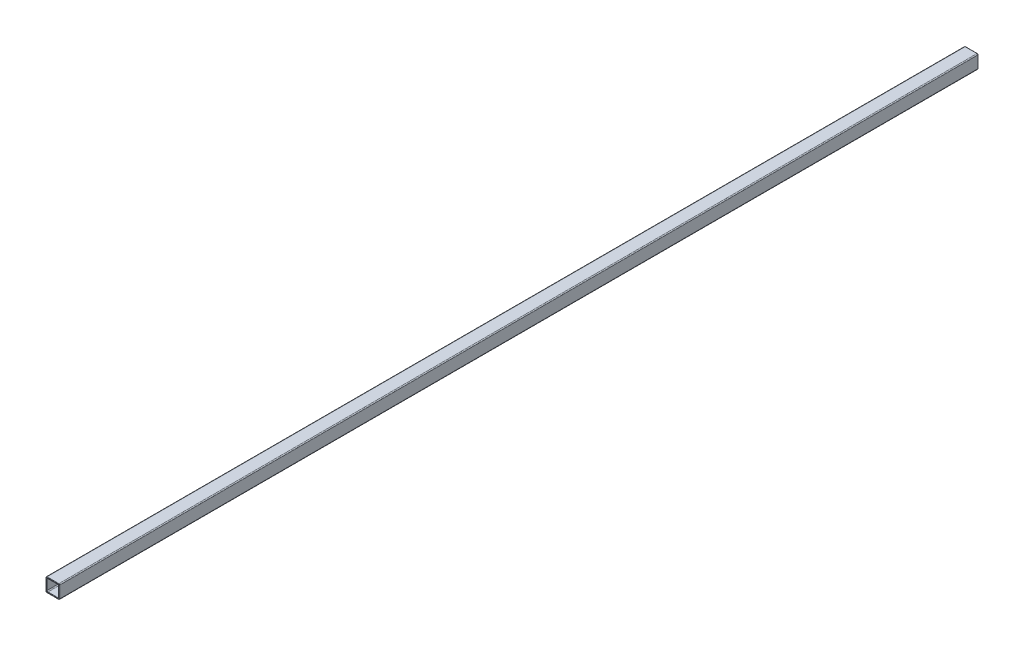
SolidWorks part; units mm, degrees
material "ASTM A500 Grade B Steel"
ref_plane "Front Plane" through (0, 0, 0) normal (0, 0, 1) x (1, 0, 0)
ref_plane "Top Plane" through (0, 0, 0) normal (0, 1, 0) x (1, 0, 0)
ref_plane "Right Plane" through (0, 0, 0) normal (1, 0, 0) x (0, 0, -1)
sketch "Sketch1" plane through (0, 0, 0) normal (0, 0, 1) x (1, 0, 0)
  line L0 (5.3086, -2.7686) -> (32.7914, -2.7686)
  line L1 (2.54, 0) -> (35.56, 0)
  line L2 (0, -2.54) -> (0, -35.56)
  line L3 (2.54, -38.1) -> (35.56, -38.1)
  line L4 (38.1, -2.54) -> (38.1, -35.56)
  line L5 (35.3314, -5.3086) -> (35.3314, -32.7914)
  line L6 (5.3086, -35.3314) -> (32.7914, -35.3314)
  line L7 (2.7686, -5.3086) -> (2.7686, -32.7914)
  line L8 (0, 0) -> (0, -38.1) construction
  line L9 (0, -38.1) -> (38.1, -38.1) construction
  line L10 (38.1, 0) -> (38.1, -38.1) construction
  line L11 (2.7686, -2.7686) -> (2.7686, -35.3314) construction
  line L12 (2.7686, -35.3314) -> (35.3314, -35.3314) construction
  line L13 (35.3314, -2.7686) -> (35.3314, -35.3314) construction
  line L14 (2.7686, -2.7686) -> (35.3314, -2.7686) construction
  line L15 (0, 0) -> (38.1, 0) construction
  arc A0 (0, -35.56) -> (2.54, -38.1) centre (2.54, -35.56) ccw
  arc A1 (38.1, -35.56) -> (35.56, -38.1) centre (35.56, -35.56) cw
  arc A2 (2.7686, -32.7914) -> (5.3086, -35.3314) centre (5.3086, -32.7914) ccw
  arc A3 (32.7914, -35.3314) -> (35.3314, -32.7914) centre (32.7914, -32.7914) ccw
  arc A4 (35.3314, -5.3086) -> (32.7914, -2.7686) centre (32.7914, -5.3086) ccw
  arc A5 (38.1, -2.54) -> (35.56, 0) centre (35.56, -2.54) ccw
  arc A6 (0, -2.54) -> (2.54, 0) centre (2.54, -2.54) cw
  arc A7 (5.3086, -2.7686) -> (2.7686, -5.3086) centre (5.3086, -5.3086) ccw
  point P12 (0, -38.1)
  dimension "D4" = 2.54
  dimension "D3" = 2.7686
extrude "Boss-Extrude1" add sketch "Sketch1" along normal blind 2570
fillet "Fillet1" radius 1 32 edges at (2.7686, -19.05, 0) (3.5125, -3.5125, 0) (19.05, -2.7686, 0) (34.5875, -3.5125, 0) (35.3314, -19.05, 0) (34.5875, -34.5875, 0) (19.05, -35.3314, 0) (3.5125, -34.5875, 0) (19.05, -38.1, 0) (37.3561, -37.3561, 0) (38.1, -19.05, 0) (37.3561, -0.7439, 0) (19.05, 0, 0) (0.7439, -0.7439, 0) (0, -19.05, 0) (0.7439, -37.3561, 0) (34.5875, -34.5875, 2570) (35.3314, -19.05, 2570) (34.5875, -3.5125, 2570) (19.05, -2.7686, 2570) (3.5125, -3.5125, 2570) (2.7686, -19.05, 2570) (3.5125, -34.5875, 2570) (19.05, -35.3314, 2570) (0, -19.05, 2570) (0.7439, -0.7439, 2570) (19.05, 0, 2570) (37.3561, -0.7439, 2570) (38.1, -19.05, 2570) (37.3561, -37.3561, 2570) (19.05, -38.1, 2570) (0.7439, -37.3561, 2570)
